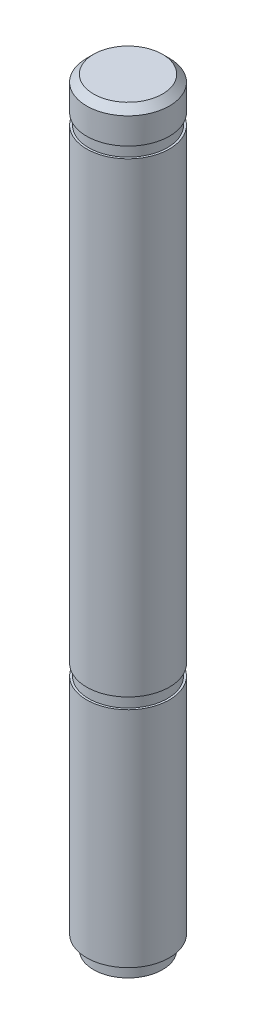
SolidWorks part; units mm, degrees
ref_plane "Płaszczyzna przednia" through (0, 0, 0) normal (0, 0, 1) x (1, 0, 0)
ref_plane "Płaszczyzna górna" through (0, 0, 0) normal (0, 1, 0) x (1, 0, 0)
ref_plane "Płaszczyzna prawa" through (0, 0, 0) normal (1, 0, 0) x (0, 0, -1)
sketch "Sketch1" plane through (0, 0, 0) normal (0, 1, 0) x (1, 0, 0)
  circle A0 centre (0, 0) radius 3
  dimension "D1" = 6
extrude "Boss-Extrude1" add sketch "Sketch1" along normal blind 40
sketch "Sketch2" plane through (0, 40, 0) normal (0, -1, 0) x (1, 0, 0)
  circle A0 centre (0, 0) radius 2.85
  circle A1 centre (0, 0) radius 3 construction
  circle A2 centre (0, 0) radius 3
  dimension "D1" = 5.7
extrude "Cut-Extrude1" cut sketch "Sketch2" against normal blind 0.8 from offset 3.2
sketch "Sketch3" plane through (0, 0, 0) normal (0, -1, 0) x (1, 0, 0)
  circle A0 centre (0, 0) radius 2.85
  circle A2 centre (0, 0) radius 3 construction
  circle A3 centre (0, 0) radius 3
  dimension "D1" = 5.7
extrude "Cut-Extrude2" cut sketch "Sketch3" against normal blind 0.8 from offset 2.2 offset against normal yes
chamfer "Chamfer1" distance 0.5 angle 45 1 edges at (0, 40, 3)
sketch "Sketch4" plane through (0, 0, 0) normal (0, -1, 0) x (1, 0, 0)
  circle A1 centre (0, 0) radius 3
  circle A2 centre (0, 0) radius 3
  dimension "D1" = 0
extrude "Boss-Extrude2" add sketch "Sketch4" along normal blind 15
sketch "Sketch5" plane through (0, -15, 0) normal (0, -1, 0) x (1, 0, 0)
  circle A0 centre (0, 0) radius 2.5
  circle A2 centre (0, 0) radius 3
  circle A3 centre (0, 0) radius 3
  dimension "D1" = 5
  dimension "D2" = 0
extrude "Cut-Extrude3" cut sketch "Sketch5" against normal blind 1
